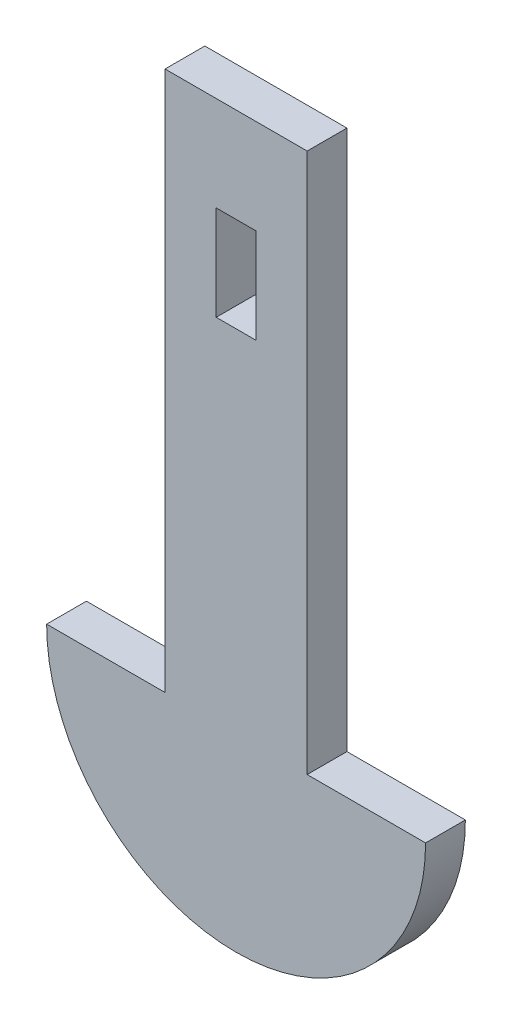
SolidWorks part; units mm, degrees
ref_plane "Front Plane" through (0, 0, 0) normal (0, 0, 1) x (1, 0, 0)
ref_plane "Top Plane" through (0, 0, 0) normal (0, 1, 0) x (1, 0, 0)
ref_plane "Right Plane" through (0, 0, 0) normal (1, 0, 0) x (0, 0, -1)
sketch "Sketch1" plane through (0, 0, 0) normal (0, 0, 1) x (1, 0, 0)
  line L0 (-25.4, 0) -> (-9.525, 0) construction
  line L1 (25.4, 0) -> (9.525, 0) construction
  line L2 (-9.525, 0) -> (-25.4, 0)
  line L3 (-9.525, 72.39) -> (-18.8973, 72.39) construction
  line L4 (-9.525, 0) -> (-9.525, 72.39)
  line L5 (-9.525, 72.39) -> (9.525, 72.39)
  line L6 (9.525, 0) -> (9.525, 72.39)
  line L8 (9.525, 0) -> (25.4, 0)
  line L9 (-18.8973, 72.39) -> (-18.8973, 59.69) construction
  line L10 (-9.525, 59.69) -> (-2.667, 59.69) construction
  line L11 (9.525, 59.69) -> (2.667, 59.69) construction
  line L13 (-2.667, 59.69) -> (2.667, 59.69)
  line L14 (-2.667, 59.69) -> (-2.667, 46.99)
  line L15 (-2.667, 46.99) -> (2.667, 46.99)
  line L16 (2.667, 59.69) -> (2.667, 46.99)
  arc A0 (-25.4, 0) -> (25.4, 0) centre (0, 0) ccw
  dimension "D1" = 50.8
  dimension "D2" = 15.875
  dimension "D3" = 15.875
  dimension "D4" = 72.39
  dimension "D5" = 12.7
  dimension "D6" = 6.858
  dimension "D7" = 6.858
  dimension "D8" = 12.7
extrude "Boss-Extrude1" add sketch "Sketch1" along normal blind 5.334
